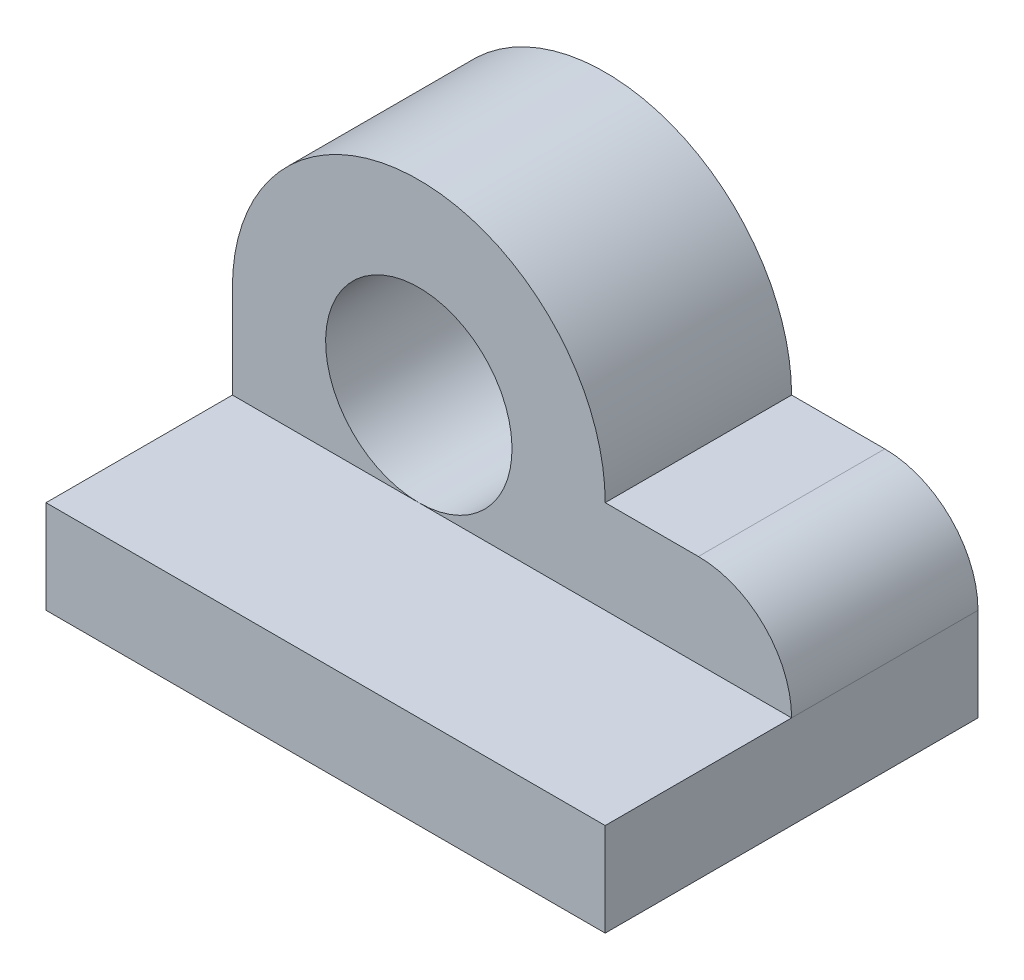
SolidWorks part; units mm, degrees
ref_plane "Ön Düzlem" through (0, 0, 0) normal (0, 0, 1) x (1, 0, 0)
ref_plane "Üst Düzlem" through (0, 0, 0) normal (0, 1, 0) x (1, 0, 0)
ref_plane "Sağ Düzlem" through (0, 0, 0) normal (1, 0, 0) x (0, 0, -1)
sketch "Sketch1" plane through (0, 0, 0) normal (0, 0, 1) x (1, 0, 0)
  line L0 (-68.4268, -7.6352) -> (-8.4268, -7.6352)
  line L1 (-68.4268, -7.6352) -> (-68.4268, 12.3648)
  line L3 (-28.4268, 12.3648) -> (-18.4268, 12.3648)
  line L4 (-8.4268, 2.3648) -> (-8.4268, -7.6352)
  arc A0 (-28.4268, 12.3648) -> (-68.4268, 12.3648) centre (-48.4268, 12.3648) ccw
  circle A1 centre (-48.4268, 12.3648) radius 10
  arc A2 (-18.4268, 12.3648) -> (-8.4268, 2.3648) centre (-18.4268, 2.3648) cw
  dimension "D1" = 10
extrude "Boss-Extrude1" add sketch "Sketch1" along normal blind 20
ref_plane "Plane1" through (0, 0, 20) normal (0, 0, 1) x (1, 0, 0)
sketch "Sketch2" plane through (0, 0, 20) normal (0, 0, 1) x (1, 0, 0)
  line L1 (-68.4268, -7.6352) -> (-8.4268, -7.6352)
  line L2 (-68.4268, -7.6352) -> (-68.4268, 2.3648)
  line L3 (-68.4268, 2.3648) -> (-8.4268, 2.3648)
  line L4 (-8.4268, -7.6352) -> (-8.4268, 2.3648)
extrude "Boss-Extrude2" add sketch "Sketch2" along normal blind 20
